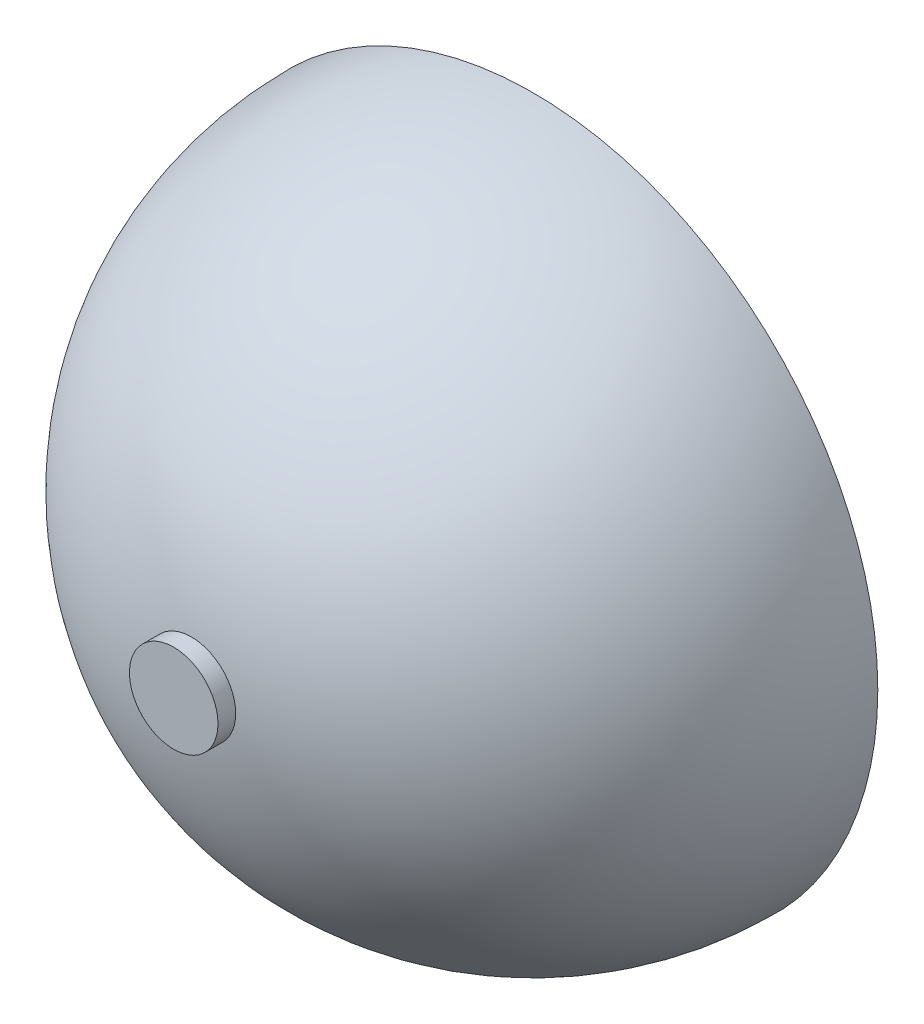
SolidWorks part; units mm, degrees
ref_plane "Plan de face" through (0, 0, 0) normal (0, 0, 1) x (1, 0, 0)
ref_plane "Plan de dessus" through (0, 0, 0) normal (0, 1, 0) x (1, 0, 0)
ref_plane "Plan de droite" through (0, 0, 0) normal (1, 0, 0) x (0, 0, -1)
sketch "Sketch1" plane through (0, 0, 0) normal (0, 1, 0) x (1, 0, 0)
  line L0 (-19.4706, 0) -> (-17.3557, 0)
  line L1 (0, -18.3094) -> (0, -17.4706)
  line L2 (-17.3557, -2) -> (-17.3557, 0)
  line L5 (0, -17.4706) -> (0, -20.3094)
  line L6 (-19.4706, 0) -> (19.4706, 0) construction
  line L7 (-17.3557, -2) -> (17.3557, -2) construction
  line L8 (0, -20.3094) -> (-2.5, -20.3094)
  line L9 (-2.5, -19.3094) -> (-2.5, -20.3094)
  arc A0 (-19.4706, 0) -> (-2.5, -19.3094) centre (0, 0) ccw
  arc A1 (-17.3557, -2) -> (0, -17.4706) centre (0, 0) ccw
  arc A3 (-17.3557, -2) -> (17.3557, -2) centre (0, 0) ccw construction
  arc A4 (-19.4706, 0) -> (19.4706, 0) centre (0, 0) ccw construction
  dimension "D1" = 2
  dimension "D2" = 2.5
  dimension "D3" = 1
revolve "Revolve4" add sketch "Sketch1" angle 360 about L0
